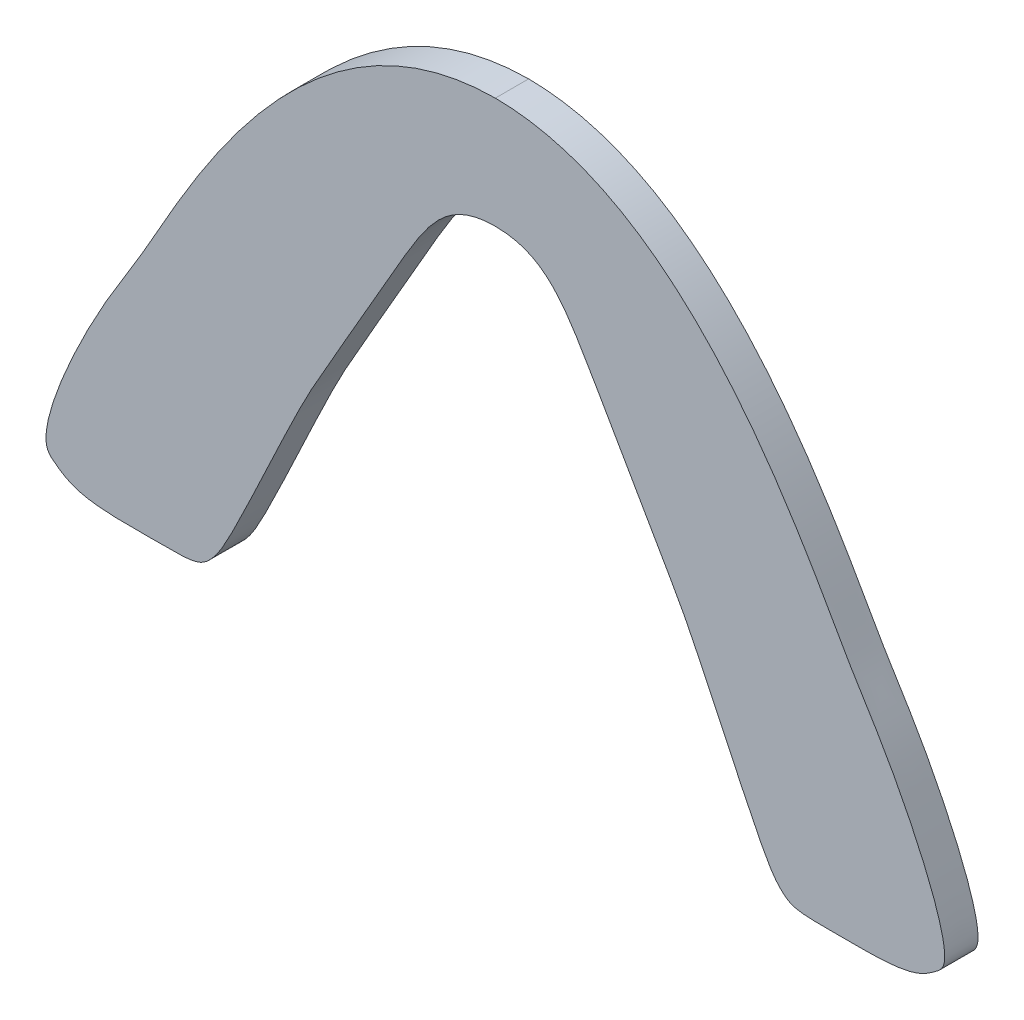
SolidWorks part; units mm, degrees
ref_plane "Front Plane" through (0, 0, 0) normal (0, 0, 1) x (1, 0, 0)
ref_plane "Top Plane" through (0, 0, 0) normal (0, 1, 0) x (1, 0, 0)
ref_plane "Right Plane" through (0, 0, 0) normal (1, 0, 0) x (0, 0, -1)
sketch "Esboço1" plane through (0, 0, 0) normal (0, 0, 1) x (1, 0, 0)
  line L0 (-40, 0) -> (33, 0) construction
  line L1 (0, -25) -> (0, 30) construction
  line L2 (3.4569, 20) -> (-3.4569, 20) construction
  line L3 (-40, -18) -> (40, -18) construction
  line L4 (34.9983, -19.8244) -> (28.8935, -19.8244) construction
  spline S0 degree 3 poles (0, 20) (4.3838, 20) (7.756, 14.4395) (15.4139, 1.0206) (18.2794, -3.9714) (23.8177, -16.5294) (26.4894, -19.9391) (27.419, -19.7967) (37.4244, -19.8568) (38.863, -18.8759) (41.7627, -16.7141) (36.7382, -5.6948) (29.7257, 4.9381) (17.1943, 29.8874) (0, 30) knots 0.303894 0.303894 0.303894 0.303894 0.33161 0.357918 0.368722 0.431773 0.448855 0.522455 0.539221 0.599748 0.617984 0.703348 0.723006 0.803894 0.803894 0.803894 0.803894
  spline S1 degree 3 poles (0, 20) (-4.3838, 20) (-7.756, 14.4395) (-15.4139, 1.0206) (-18.2794, -3.9714) (-23.8177, -16.5294) (-26.4894, -19.9391) (-27.419, -19.7967) (-37.4244, -19.8568) (-38.863, -18.8759) (-41.7627, -16.7141) (-36.7382, -5.6948) (-29.7257, 4.9381) (-17.1943, 29.8874) (0, 30) knots 0.303894 0.303894 0.303894 0.303894 0.33161 0.357918 0.368722 0.431773 0.448855 0.522455 0.539221 0.599748 0.617984 0.703348 0.723006 0.803894 0.803894 0.803894 0.803894
  point P3 (33, -21.1402)
  point P6 (35.1565, -21.1442)
  point P9 (0, 0)
  point P10 (35.5044, -23.2207)
  point P11 (0, -18)
  point P12 (25, -18)
  point P13 (16, 0)
  point P14 (0, -20)
  point P15 (0, 20)
  point P18 (33.6264, -20.3032)
  point P22 (35.9209, -19.6319)
  point P25 (0, 0)
  point P26 (36.9284, -20.3785)
  point P27 (33, -19.8437)
  point P32 (0, 0)
  dimension "D3" = 40
  dimension "D5" = 33
  dimension "D7" = 18
  dimension "D9" = 30
  dimension "D10" = 20
  dimension "D11" = 16
  dimension "D13" = 25
extrude "Ressalto-extrusão1" add sketch "Esboço1" along normal blind 3
